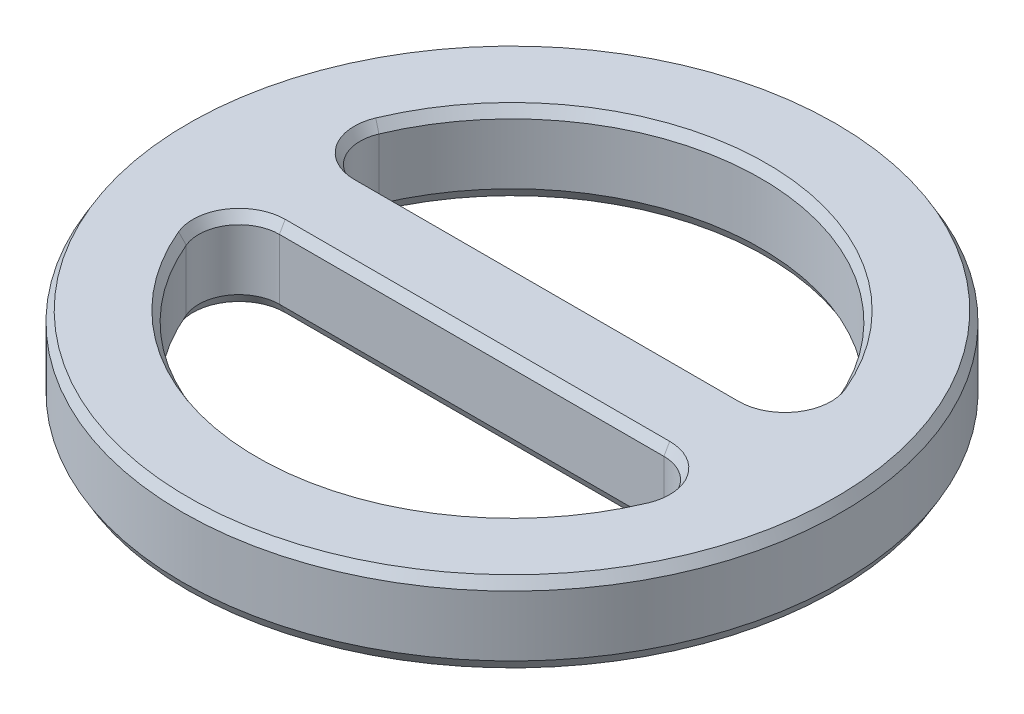
SolidWorks part; units mm, degrees
ref_plane "Front Plane" through (0, 0, 0) normal (0, 0, 1) x (1, 0, 0)
ref_plane "Top Plane" through (0, 0, 0) normal (0, 1, 0) x (1, 0, 0)
ref_plane "Right Plane" through (0, 0, 0) normal (1, 0, 0) x (0, 0, -1)
sketch "Sketch1" plane through (0, 0, 0) normal (0, 1, 0) x (1, 0, 0)
  line L0 (-73.0205, 12) -> (73.0205, 12)
  line L1 (73.0205, -12) -> (-73.0205, -12)
  circle A0 centre (0, 0) radius 98
  arc A1 (73.0205, 12) -> (-73.0205, 12) centre (0, 0) ccw
  arc A2 (-73.0205, -12) -> (73.0205, -12) centre (0, 0) ccw
  point P8 (0, 0)
  dimension "D1" = 196
  dimension "D2" = 24
  dimension "D3" = 24
  dimension "D4" = 12
extrude "Boss-Extrude1" add sketch "Sketch1" along normal blind 24
fillet "Fillet1" radius 12 4 edges at (-73.0205, 12, 12) (73.0205, 12, 12) (-73.0205, 12, -12) (73.0205, 12, -12)
chamfer "Chamfer1" distance 3 angle 30 9 edges at (0, 24, 98) (0, 0, -12) (67.16, 0, -17.357) (-67.16, 0, -17.357) (0, 0, -74) (0, 0, 74) (67.16, 0, 17.357) (-67.16, 0, 17.357) (0, 0, 12)
chamfer "Chamfer2" distance 3 angle 30 9 edges at (0, 0, 98) (0, 24, -74) (-67.16, 24, -17.357) (67.16, 24, -17.357) (0, 24, -12) (0, 24, 74) (67.16, 24, 17.357) (-67.16, 24, 17.357) (0, 24, 12)
